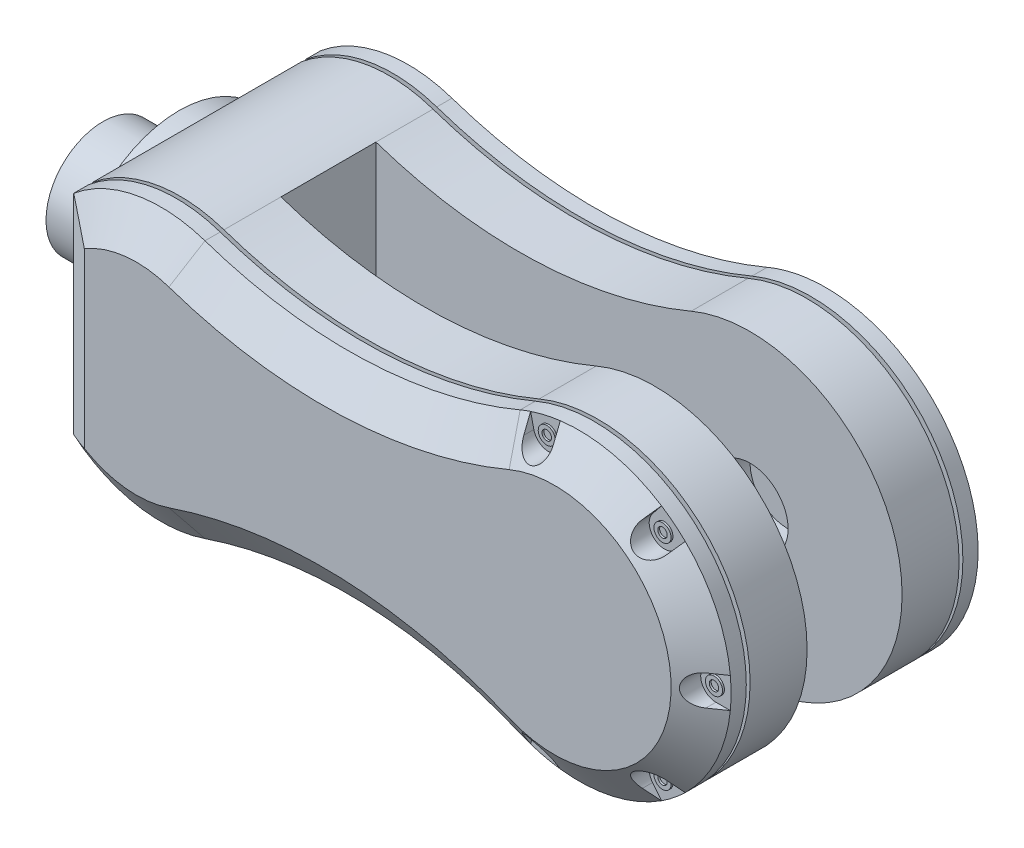
SolidWorks part; units mm, degrees
ref_plane "Front Plane" through (0, 0, 0) normal (0, 0, 1) x (1, 0, 0)
ref_plane "Top Plane" through (0, 0, 0) normal (0, 1, 0) x (1, 0, 0)
ref_plane "Right Plane" through (0, 0, 0) normal (1, 0, 0) x (0, 0, -1)
sketch "Sketch1" plane through (0, 0, 0) normal (1, 0, 0) x (0, 0, -1)
  circle A0 centre (0, 0) radius 27.5
  dimension "D1" = 55
extrude "Boss-Extrude1" add sketch "Sketch1" along normal blind 5
ref_plane "Plane1" through (0, 0, 12.7) normal (0, 0, 1) x (1, 0, 0)
sketch "Sketch2" plane through (0, 0, 12.7) normal (0, 0, 1) x (1, 0, 0)
  line L1 (5, 27.5) -> (5, -27.5)
  line L3 (5, -27.5) -> (5, 27.5) construction
  arc A1 (122.49, -36.8706) -> (122.49, 36.8706) centre (138, 0) ccw
  arc A2 (5, -27.5) -> (39.537, -33.9433) centre (28, 0) ccw
  arc A3 (39.537, 33.9433) -> (122.49, 36.8706) centre (77.1591, 144.6322) ccw
  arc A4 (39.537, -33.9433) -> (122.49, -36.8706) centre (77.1591, -144.6322) cw
  arc A5 (39.537, 33.9433) -> (5, 27.5) centre (28, 0) ccw
  dimension "D3" = 80
  dimension "D2" = 110
extrude "Boss-Extrude2" add sketch "Sketch2" along normal blind 15
sketch "Sketch3" plane through (0, 0, 27.7) normal (0, 0, 1) x (1, 0, 0)
  line L2 (7.5, 26.3059) -> (7.5, -26.3059)
  line L3 (7.5, 26.3059) -> (7.5, -26.3059)
  arc A10 (38.7325, 31.5763) -> (7.5, 26.3059) centre (28, 0) ccw
  arc A11 (7.5, -26.3059) -> (38.7325, -31.5763) centre (28, 0) ccw
  arc A12 (123.4594, -34.5662) -> (38.7325, -31.5763) centre (77.1591, -144.6322) ccw
  arc A13 (123.4594, -34.5662) -> (123.4594, 34.5662) centre (138, 0) ccw
  arc A14 (38.7325, 31.5763) -> (123.4594, 34.5662) centre (77.1591, 144.6322) ccw
  arc A15 (38.7325, 31.5763) -> (7.5, 26.3059) centre (28, 0) ccw
  arc A16 (7.5, -26.3059) -> (38.7325, -31.5763) centre (28, 0) ccw
  arc A17 (123.4594, -34.5662) -> (38.7325, -31.5763) centre (77.1591, -144.6322) ccw
  arc A18 (123.4594, -34.5662) -> (123.4594, 34.5662) centre (138, 0) ccw
  arc A19 (38.7325, 31.5763) -> (123.4594, 34.5662) centre (77.1591, 144.6322) ccw
  dimension "D1" = 2.5
extrude "Boss-Extrude3" add sketch "Sketch3" along normal blind 1
sketch "Sketch5" plane through (0, 0, 28.7) normal (0, 0, 1) x (1, 0, 0)
  line L1 (5, 27.5) -> (5, -27.5)
  line L2 (5, 27.5) -> (5, -27.5)
  arc A5 (39.537, 33.9433) -> (5, 27.5) centre (28, 0) ccw
  arc A6 (5, -27.5) -> (39.537, -33.9433) centre (28, 0) ccw
  arc A7 (122.49, -36.8706) -> (39.537, -33.9433) centre (77.1591, -144.6322) ccw
  arc A8 (122.49, -36.8706) -> (122.49, 36.8706) centre (138, 0) ccw
  arc A9 (39.537, 33.9433) -> (122.49, 36.8706) centre (77.1591, 144.6322) ccw
  arc A10 (39.537, 33.9433) -> (5, 27.5) centre (28, 0) ccw
  arc A11 (5, -27.5) -> (39.537, -33.9433) centre (28, 0) ccw
  arc A12 (122.49, -36.8706) -> (39.537, -33.9433) centre (77.1591, -144.6322) ccw
  arc A13 (122.49, -36.8706) -> (122.49, 36.8706) centre (138, 0) ccw
  arc A14 (39.537, 33.9433) -> (122.49, 36.8706) centre (77.1591, 144.6322) ccw
  dimension "D1" = 0
extrude "Boss-Extrude5" add sketch "Sketch5" along normal blind 4
sketch "Sketch6" plane through (0, 0, 32.7) normal (0, 0, 1) x (1, 0, 0)
  line L1 (5, 27.5) -> (5, -27.5)
  line L2 (5, 27.5) -> (5, -27.5)
  arc A5 (39.537, 33.9433) -> (122.49, 36.8706) centre (77.1591, 144.6322) ccw
  arc A6 (39.537, 33.9433) -> (5, 27.5) centre (28, 0) ccw
  arc A7 (5, -27.5) -> (39.537, -33.9433) centre (28, 0) ccw
  arc A8 (122.49, -36.8706) -> (39.537, -33.9433) centre (77.1591, -144.6322) ccw
  arc A9 (122.49, -36.8706) -> (122.49, 36.8706) centre (138, 0) ccw
  arc A10 (39.537, 33.9433) -> (122.49, 36.8706) centre (77.1591, 144.6322) ccw
  arc A11 (39.537, 33.9433) -> (5, 27.5) centre (28, 0) ccw
  arc A12 (5, -27.5) -> (39.537, -33.9433) centre (28, 0) ccw
  arc A13 (122.49, -36.8706) -> (39.537, -33.9433) centre (77.1591, -144.6322) ccw
  arc A14 (122.49, -36.8706) -> (122.49, 36.8706) centre (138, 0) ccw
  dimension "D1" = 0
extrude "Boss-Extrude6" add sketch "Sketch6" along normal blind 6.5 draft 55
sketch "Sketch7" plane through (0, 0, 39.2) normal (0, 0, 1) x (1, 0, 0)
  line L0 (5, 0) -> (170, 0) construction
  line L1 (5, 24.3918) -> (5, -24.3918) construction
  line L3 (174, 4) -> (179.4236, 4)
  line L4 (179.4236, 4) -> (179.4236, -4)
  line L5 (179.4236, -4) -> (174, -4)
  line L6 (179.4236, 0) -> (205.4292, 0) construction
  arc A1 (174, 4) -> (174, -4) centre (174, 0) ccw
extrude "Cut-Extrude1" cut sketch "Sketch7" against normal blind 6.5
sketch "Sketch8" plane through (0, 0, 32.7) normal (0, 0, 1) x (1, 0, 0)
  line L0 (170, 0) -> (178, 0) construction
  arc A0 (174, 4) -> (174, -4) centre (174, 0) ccw construction
  arc A1 (177.7995, -4) -> (177.7995, 4) centre (138, 0) ccw construction
  circle A2 centre (174, 0) radius 2.25
  circle A3 centre (174, 0) radius 1.25
  dimension "D1" = 2.5
  dimension "D2" = 1
extrude "Boss-Extrude7" add sketch "Sketch8" along normal blind 0.5
pattern_circular "CirPattern1" count 7 over 360 about axis through (138, 0, 0) along (0, 0, 1) skipping 3, 4 of "Boss-Extrude7", "Cut-Extrude1"
sketch "Sketch9" plane through (0, 0, 12.7) normal (0, 0, -1) x (-1, 0, 0)
  line L0 (-39.537, 33.9433) -> (-39.537, -33.9433)
  line L4 (-5, -27.5) -> (-5, -24.3918)
  line L5 (-5, -24.3918) -> (-5, 24.3918)
  line L6 (-5, 24.3918) -> (-5, 27.5)
  line L7 (-5, -27.5) -> (-5, -24.3918)
  line L8 (-5, -24.3918) -> (-5, 24.3918)
  line L9 (-5, 24.3918) -> (-5, 27.5)
  arc A5 (-5, 27.5) -> (-39.537, 33.9433) centre (-28, 0) ccw
  arc A6 (-122.49, 36.8706) -> (-39.537, 33.9433) centre (-77.1591, 144.6322) ccw
  arc A7 (-122.49, 36.8706) -> (-122.49, -36.8706) centre (-138, 0) ccw
  arc A8 (-39.537, -33.9433) -> (-122.49, -36.8706) centre (-77.1591, -144.6322) ccw
  arc A9 (-39.537, -33.9433) -> (-5, -27.5) centre (-28, 0) ccw
  arc A10 (-5, 27.5) -> (-39.537, 33.9433) centre (-28, 0) ccw
  arc A14 (-39.537, -33.9433) -> (-5, -27.5) centre (-28, 0) ccw
  dimension "D1" = 0
extrude "Boss-Extrude9" add sketch "Sketch9" along normal blind 40
ref_plane "Plane3" through (0, 0, 0.2) normal (0, 0, -1) x (-1, 0, 0)
mirror "Mirror2" about plane through (0, 0, 0.2) normal (0, 0, -1) of "Boss-Extrude9", "CirPattern1", "Cut-Extrude1", "Boss-Extrude7", "Boss-Extrude6", "Boss-Extrude3", "Boss-Extrude5", "Boss-Extrude2"
sketch "Sketch11" plane through (0, 0, 0) normal (-1, 0, 0) x (0, 0, 1)
  circle A0 centre (0, 0) radius 15
  dimension "D1" = 30
extrude "Boss-Extrude10" add sketch "Sketch11" along normal blind 20
sketch "Sketch12" plane through (0, 0, -12.3) normal (0, 0, 1) x (1, 0, 0)
  circle A0 centre (138, 0) radius 10
  dimension "D1" = 20
extrude "Cut-Extrude2" cut sketch "Sketch12" against normal blind 10
sketch "Sketch13" plane through (0, 0, 12.7) normal (0, 0, -1) x (-1, 0, 0)
  circle A0 centre (-138, 0) radius 10
  dimension "D1" = 20
extrude "Cut-Extrude3" cut sketch "Sketch13" against normal blind 10
